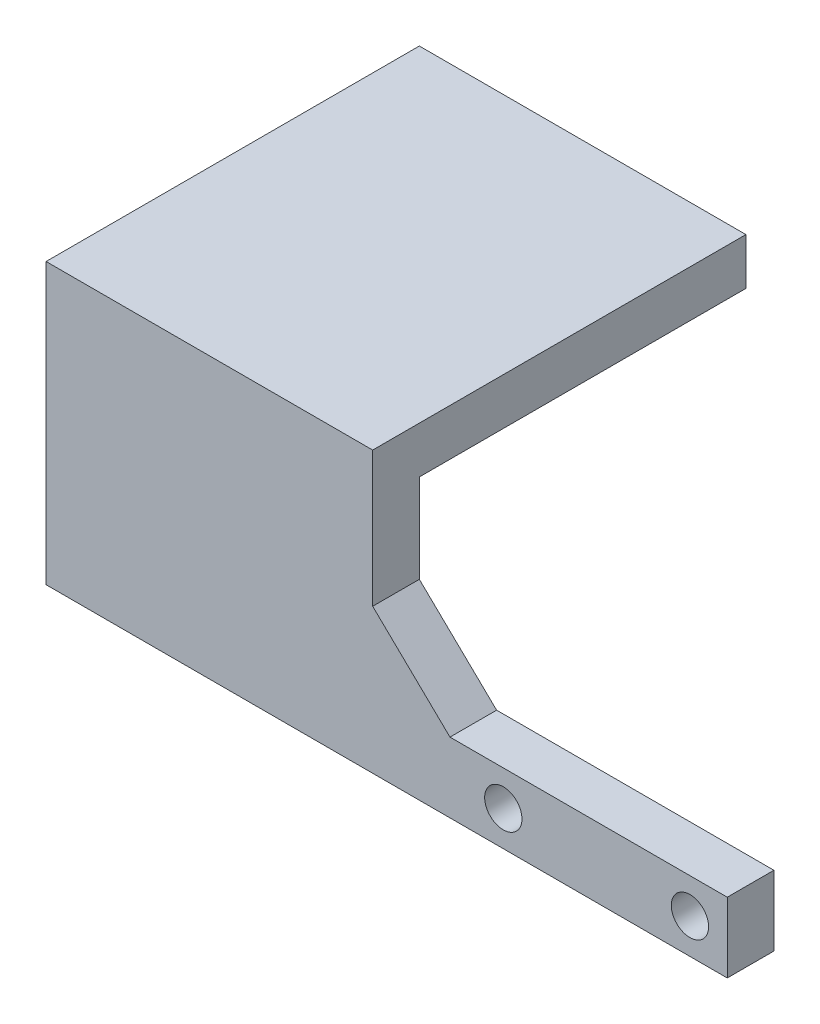
SolidWorks part; units mm, degrees
ref_plane "Top Plane" through (0, 0, 0) normal (0, 0, 1) x (1, 0, 0)
ref_plane "Right Plane" through (0, 0, 0) normal (0, 1, 0) x (1, 0, 0)
ref_plane "Front Plane" through (0, 0, 0) normal (1, 0, 0) x (0, 0, -1)
sketch "Sketch1" plane through (0, 0, 0) normal (0, 0, 1) x (1, 0, 0)
  line L0 (-10, 0) -> (10, 0) construction
  line L1 (-14, 3.75) -> (14, 3.75)
  line L3 (-14, -3.75) -> (14, -3.75)
  line L4 (14, 3.75) -> (14, -3.75)
  line L5 (-14, 3.75) -> (14, -3.75) construction
  line L6 (-14, -3.75) -> (14, 3.75) construction
  line L8 (-14, 3.75) -> (-59, 3.75)
  line L9 (-14, 3.75) -> (-14, -3.75) construction
  line L10 (-14, -3.75) -> (-59, -3.75)
  line L11 (-59, 3.75) -> (-59, -3.75)
  circle A0 centre (-10, 0) radius 2
  circle A1 centre (10, 0) radius 2
  point P4 (0, 0)
  point P13 (-14, -4.518)
  dimension "D1" = 4
  dimension "D2" = 20
  dimension "D3" = 28
  dimension "D4" = 7.5
  dimension "D5" = 45
extrude "Boss-Extrude1" add sketch "Sketch1" along normal blind 5
sketch "Sketch2" plane through (-59, 0, 0) normal (-1, 0, 0) x (0, 0, 1)
  line L0 (0, 3.75) -> (0, 21.25)
  line L1 (0, 21.25) -> (-35, 21.25)
  line L2 (-35, 21.25) -> (-35, 26.25)
  line L3 (-35, 26.25) -> (5, 26.25)
  line L4 (5, 26.25) -> (5, 3.75)
  line L5 (5, -3.75) -> (0, -3.75) construction
  line L6 (5, 3.75) -> (0, 3.75) construction
  line L7 (0, 3.75) -> (5, 3.75)
  dimension "D1" = 25
  dimension "D2" = 35
extrude "Boss-Extrude2" add sketch "Sketch2" against normal blind 35
chamfer "Chamfer1" distance 8 angle 46 1 edges at (-24, 3.75, 2.5)
